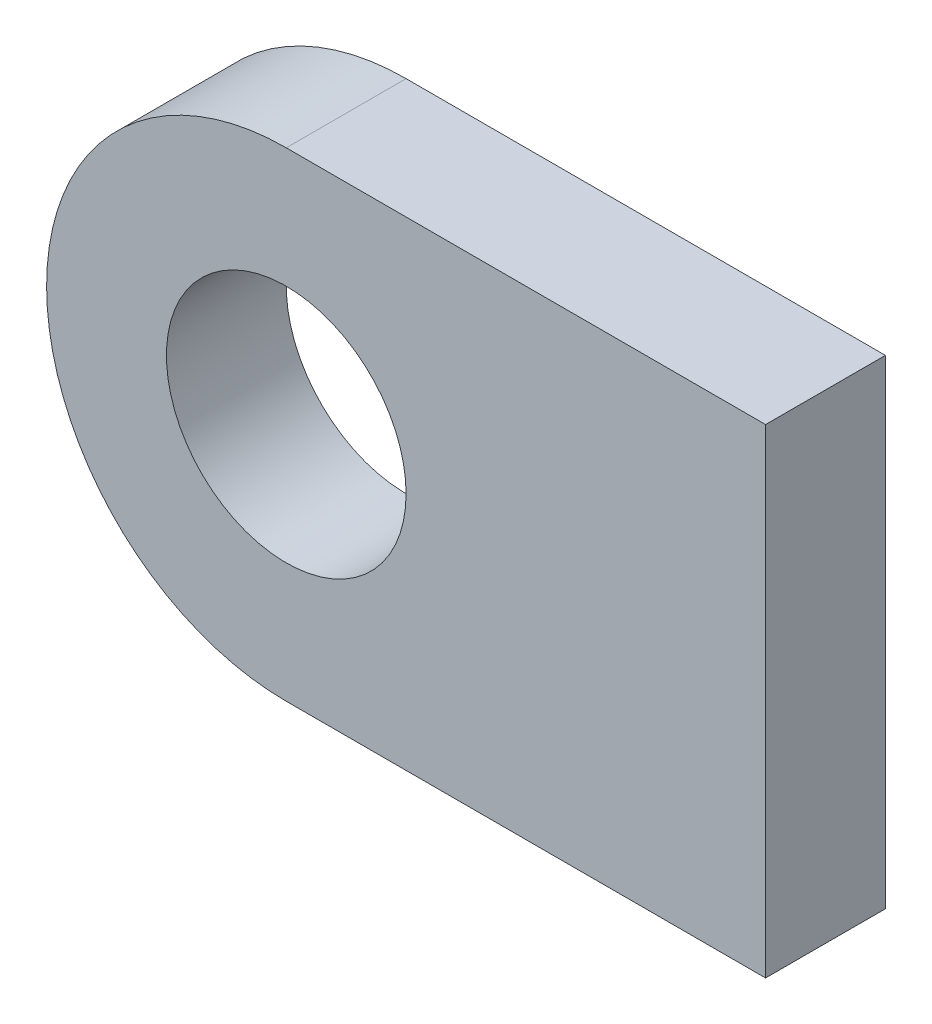
SolidWorks part; units mm, degrees
material "201 Annealed Stainless Steel (SS)"
ref_plane "Front Plane" through (0, 0, 0) normal (0, 0, 1) x (1, 0, 0)
ref_plane "Top Plane" through (0, 0, 0) normal (0, 1, 0) x (1, 0, 0)
ref_plane "Right Plane" through (0, 0, 0) normal (1, 0, 0) x (0, 0, -1)
sketch "Sketch4" plane through (0, 0, 0) normal (0, 0, 1) x (1, 0, 0)
  line L1 (-33.5489, 10) -> (-13.5489, 10)
  line L3 (-33.5489, -10) -> (-13.5489, -10)
  line L4 (-13.5489, 10) -> (-13.5489, -10)
  arc A0 (-33.5489, 10) -> (-33.5489, -10) centre (-33.5489, 0) ccw
  point P0 (0, 0)
  point P7 (0, 0)
extrude "Boss-Extrude2" add sketch "Sketch4" along normal blind 5 contours L1 L4 L3 A0
hole_wizard "Ø10.0mm Dowel Hole1" positions "Sketch9" profile "Sketch10" hole size "Ø10.0" standard "ANSI Metric"
sketch "Sketch9" plane through (0, 0, 5) normal (0, 0, 1) x (1, 0, 0)
  point P0 (-33.5489, 0)
sketch "Sketch10" plane through (-33.5489, 0, 5) normal (1, 0, 0) x (0, -1, 0)
  line L0 (0, 0) -> (0, 13.0043)
  line L1 (0, 13.0043) -> (5, 10)
  line L2 (5, 10) -> (5, 0)
  line L5 (5, 0) -> (0, 0)
  line L10 (0, 13.0043) -> (-5, 10) construction
  line L11 (0, -6.35) -> (0, 107.95) construction
  dimension "Hole Dia." = 10
  dimension "Hole Depth" = 10
  dimension "Drill Angle" = 118
